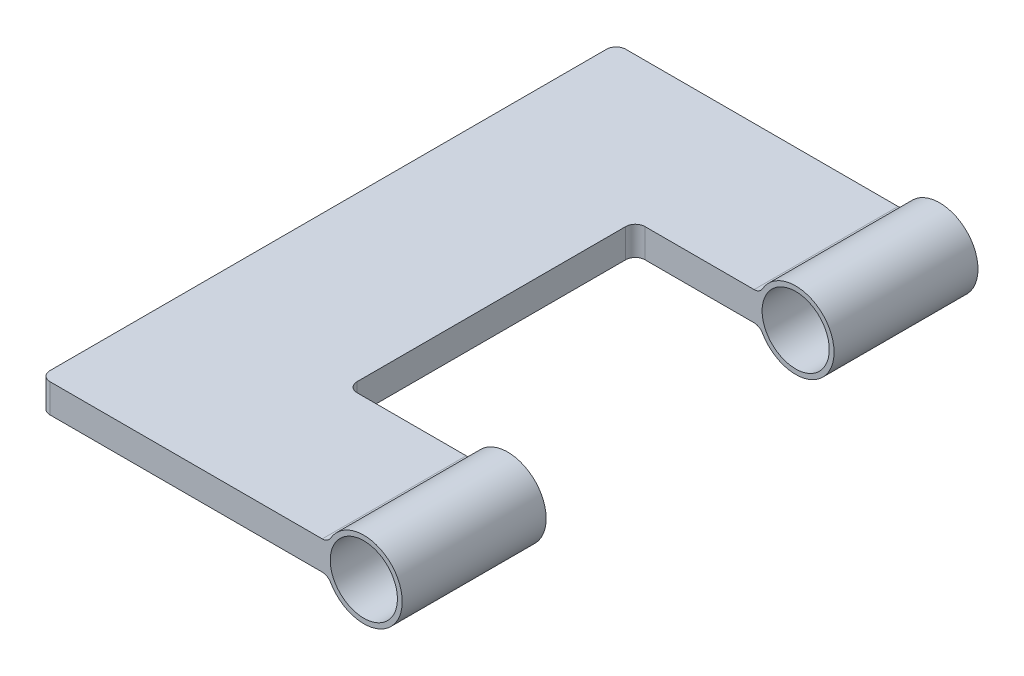
SolidWorks part; units mm, degrees
ref_plane "Front Plane" through (0, 0, 0) normal (0, 0, 1) x (1, 0, 0)
ref_plane "Top Plane" through (0, 0, 0) normal (0, 1, 0) x (1, 0, 0)
ref_plane "Right Plane" through (0, 0, 0) normal (1, 0, 0) x (0, 0, -1)
sketch "Sketch3" plane through (0, 0, 0) normal (0, 0, 1) x (1, 0, 0)
  line L1 (0, 0) -> (150, 0)
  line L2 (0, 0) -> (0, 15)
  line L3 (0, 15) -> (150, 15)
  arc A0 (150, 0) -> (150, 15) centre (168.5405, 7.5) ccw
  point P7 (0, 7.5)
  dimension "D3" = 20
  dimension "D1" = 150
  dimension "D2" = 15
extrude "Boss-Extrude2" add sketch "Sketch3" along normal mid plane 300
sketch "Sketch4" plane through (0, 0, 0) normal (0, 1, 0) x (1, 0, 0)
  line L1 (85, -75) -> (195, -75)
  line L2 (85, -75) -> (85, 75)
  line L3 (85, 75) -> (195, 75)
  line L4 (195, -75) -> (195, 75)
  point P4 (0, 0)
  point P5 (85, 0)
  dimension "D1" = 150
  dimension "D2" = 110
  dimension "D3" = 85
extrude "Cut-Extrude1" cut sketch "Sketch4" against normal mid plane 300
fillet "Fillet1" radius 5 8 edges at (0, 7.5, -150) (0, 7.5, 150) (150, 0, -112.5) (150, 0, 112.5) (150, 15, 112.5) (150, 15, -112.5) (85, 7.5, 75) (85, 7.5, -75)
sketch "Sketch5" plane through (0, 0, 150) normal (0, 0, 1) x (1, 0, 0)
  arc A0 (151.22, -2.5) -> (151.22, 17.5) centre (168.5405, 7.5) ccw construction
  arc A1 (151.22, -2.5) -> (151.22, 17.5) centre (168.5405, 7.5) ccw construction
  circle A2 centre (168.5405, 7.5) radius 17.5
  dimension "D1" = 35
extrude "Cut-Extrude2" cut sketch "Sketch5" against normal mid plane 756
